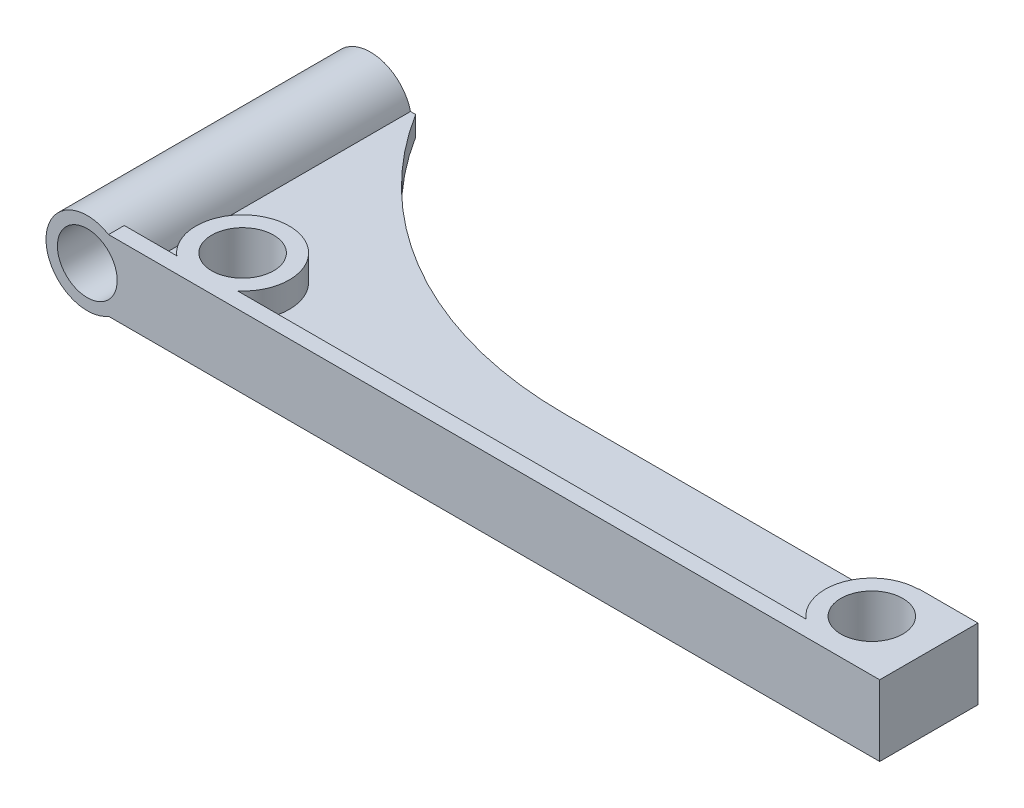
SolidWorks part; units mm, degrees
ref_plane "Front" through (0, 0, 0) normal (0, 0, 1) x (1, 0, 0)
ref_plane "Top" through (0, 0, 0) normal (0, 1, 0) x (1, 0, 0)
ref_plane "Right" through (0, 0, 0) normal (1, 0, 0) x (0, 0, -1)
sketch "Sketch1" plane through (0, 0, 0) normal (0, 0, 1) x (1, 0, 0)
  circle A0 centre (0, 0) radius 10.5
  dimension "D1" = 21
extrude "Boss-Extrude1" add sketch "Sketch1" against normal blind 72
sketch "Sketch2" plane through (0, 0, 0) normal (0, 0, 1) x (1, 0, 0)
  circle A0 centre (0, 0) radius 7.6
  dimension "D1" = 15.2
extrude "Cut-Extrude5" cut sketch "Sketch2" against normal through all
sketch "Sketch3" plane through (0, 0, 0) normal (0, 0, 1) x (1, 0, 0)
  line L1 (5.4083, 9) -> (201.5, 9)
  line L3 (5.4083, -9) -> (201.5, -9)
  line L4 (201.5, 9) -> (201.5, -9)
  circle A0 centre (0, 0) radius 10.5 construction
  arc A1 (5.4083, -9) -> (5.4083, 9) centre (0, 0) ccw
  point P7 (201.5, 0)
  dimension "D2" = 201.5
  dimension "D1" = 18
extrude "Boss-Extrude2" add sketch "Sketch3" against normal blind 72
sketch "Sketch4" plane through (0, 0, -72) normal (0, 0, -1) x (-1, 0, 0)
  line L0 (-201.5, -9) -> (-201.5, 9) construction
  line L1 (-201.5, 2.5) -> (-10.198, 2.5)
  line L2 (-201.5, 2.5) -> (-201.5, -2.5) construction
  line L3 (-201.5, -2.5) -> (-10.198, -2.5) construction
  line L4 (-201.5, 9) -> (5.4083, 9)
  line L5 (-201.5, 9) -> (-5.4083, 9) construction
  line L6 (-201.5, 2.5) -> (-201.5, 9)
  arc A0 (-5.4083, -9) -> (-5.4083, 9) centre (0, 0) ccw construction
  arc A1 (-4.6579, 9.4103) -> (-10.198, -2.5) centre (0, 0) ccw construction
  arc A2 (-10.198, 2.5) -> (5.4083, 9) centre (0, 0) cw
  point P6 (-201.5, 0)
  line M6 (-5.4083, 9) -> (-201.5, 9)
  line M7 (-201.5, 9) -> (-201.5, -9)
  dimension "D1" = 5
extrude "Cut-Extrude2" cut sketch "Sketch4" against normal blind 68 contours L1 A2 M6 M7
mirror "Mirror1" about plane through (0, 0, 0) normal (0, 1, 0) of "Cut-Extrude2"
sketch "Sketch5" plane through (0, 2.5, 0) normal (0, 1, 0) x (1, 0, 0)
  line L0 (201.5, 72) -> (10.198, 72) construction
  line L1 (96.2998, 25) -> (201.5, 25)
  line L2 (201.5, 4) -> (201.5, 72) construction
  line L3 (201.5, 72) -> (11.5, 72)
  line L4 (201.5, 0) -> (5.4083, 0) construction
  line L5 (201.5, 72) -> (201.5, 25)
  arc A0 (11.5, 72) -> (96.2998, 25) centre (96.2998, 125) ccw
  dimension "D2" = 100
  dimension "D1" = 25
  dimension "D3" = 190
extrude "Cut-Extrude3" cut sketch "Sketch5" against normal through all
sketch "Sketch6" plane through (0, -2.5, 0) normal (0, -1, 0) x (1, 0, 0)
  line L0 (201.5, -4) -> (201.5, -25) construction
  line L1 (5.4083, 0) -> (201.5, 0) construction
  circle A0 centre (186.5, -13) radius 7.875
  circle A1 centre (26.5, -13) radius 7.875
  dimension "D1" = 15.75
  dimension "D3" = 160
  dimension "D2" = 15
  dimension "D4" = 13
extrude "Cut-Extrude4" cut sketch "Sketch6" against normal through all
sketch "Sketch7" plane through (0, -2.5, 0) normal (0, -1, 0) x (1, 0, 0)
  circle A0 centre (26.5, -13) radius 7.875 construction
  circle A1 centre (186.5, -13) radius 7.875 construction
  circle A2 centre (26.5, -13) radius 7.875
  circle A3 centre (186.5, -13) radius 7.875
extrude "Extrude-Thin1" add sketch "Sketch7" along normal blind 6.5 thin
sketch "Sketch8" plane through (0, -2.5, 0) normal (0, -1, 0) x (1, 0, 0)
  line L1 (201.5, -4) -> (201.5, -25) construction
  line L3 (201.5, -4) -> (194.247, -4)
  line L4 (201.5, -4) -> (201.5, -25)
  line L5 (201.5, -25) -> (186.5, -25)
  line L6 (186.5, -25) -> (186.5, -24.875)
  line L7 (201.5, -25) -> (96.2998, -25) construction
  arc A1 (178.753, -4) -> (194.247, -4) centre (186.5, -13) ccw construction
  arc A2 (186.5, -24.875) -> (194.247, -4) centre (186.5, -13) ccw
  arc A3 (178.753, -4) -> (194.247, -4) centre (186.5, -13) ccw construction
extrude "Boss-Extrude3" add sketch "Sketch8" along normal blind 6.5
mirror "Mirror2" about plane through (0, 0, 0) normal (0, 1, 0) of "Boss-Extrude3", "Extrude-Thin1"
